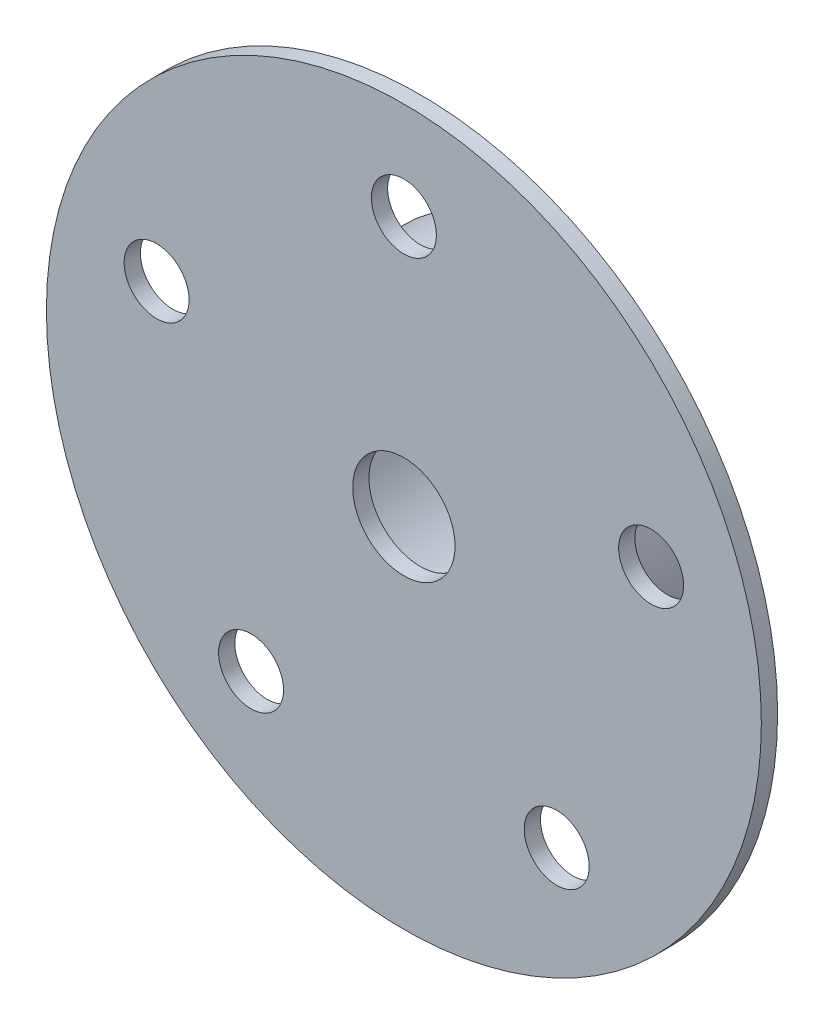
SolidWorks part; units mm, degrees
ref_plane "前视基准面" through (0, 0, 0) normal (0, 0, 1) x (1, 0, 0)
ref_plane "上视基准面" through (0, 0, 0) normal (0, 1, 0) x (1, 0, 0)
ref_plane "右视基准面" through (0, 0, 0) normal (1, 0, 0) x (0, 0, -1)
other "Configuration Table"
sketch "草图1" plane through (0, 0, 0) normal (0, 0, 1) x (1, 0, 0)
  circle A4 centre (0, 0) radius 3.15
  circle A5 centre (0, 0) radius 22
  circle A6 centre (0, 0) radius 16 construction
  circle A8 centre (0, 16) radius 2
  circle A9 centre (15.2169, 4.9443) radius 2
  circle A10 centre (9.4046, -12.9443) radius 2
  circle A11 centre (-9.4046, -12.9443) radius 2
  circle A12 centre (-15.2169, 4.9443) radius 2
  point P0 (0, 0)
  point P17 (0, 0)
  point P19 (0, 0)
  dimension "D3" = 5
  dimension "D5" = 4
  dimension "D1" = 44
  dimension "D2" = 32
  dimension "D4" = 6.3
extrude "凸台-拉伸1" add sketch "草图1" along normal blind 1
sketch "草图3" plane through (0, 0, 0) normal (0, 0, -1) x (-1, 0, 0)
  circle A0 centre (0, 0) radius 11
  circle A1 centre (0, 0) radius 7.6
  dimension "D1" = 22
  dimension "D2" = 15.2
extrude "凸台-拉伸2" add sketch "草图3" along normal blind 7
